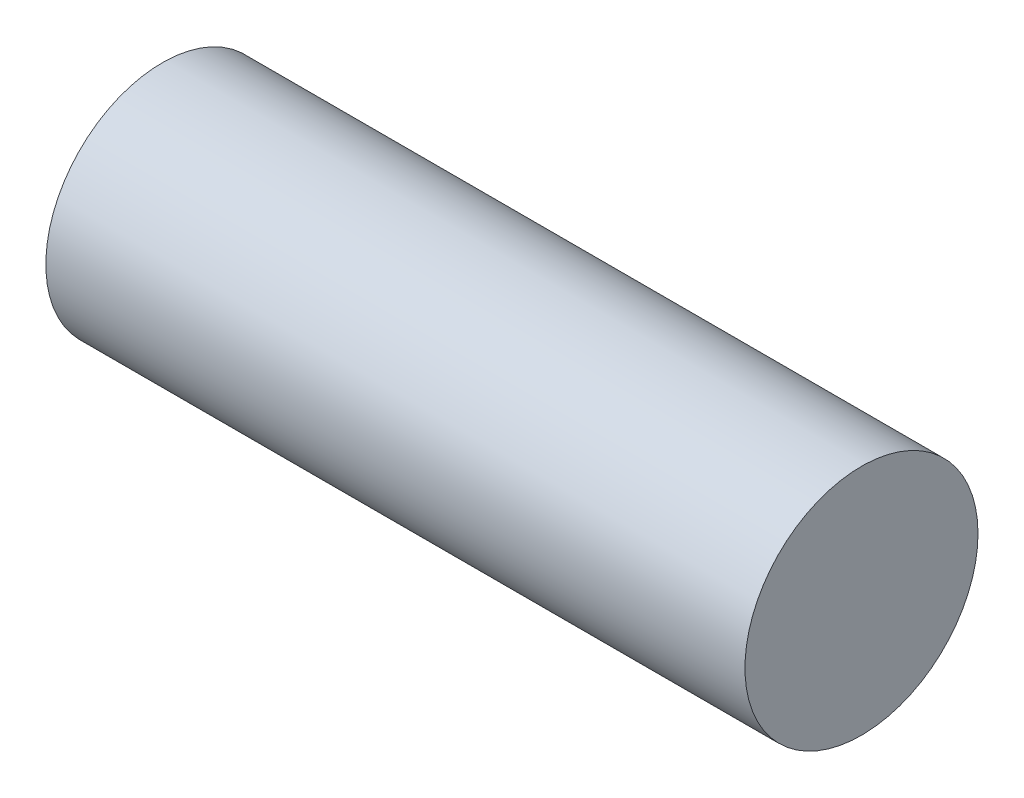
SolidWorks part; units mm, degrees
ref_plane "Front Plane" through (0, 0, 0) normal (0, 0, 1) x (1, 0, 0)
ref_plane "Top Plane" through (0, 0, 0) normal (0, 1, 0) x (1, 0, 0)
ref_plane "Right Plane" through (0, 0, 0) normal (1, 0, 0) x (0, 0, -1)
sketch "Sketch1" plane through (0, 0, 0) normal (1, 0, 0) x (0, 0, -1)
  circle A0 centre (0, 0) radius 5
  dimension "D1" = 10
extrude "Boss-Extrude1" add sketch "Sketch1" along normal blind 30
sketch "Sketch2" plane through (0, 0, 0) normal (-1, 0, 0) x (0, 0, 1)
  circle A0 centre (0, 0) radius 1.5
  dimension "D1" = 3
extrude "Cut-Extrude1" cut sketch "Sketch2" against normal blind 20
